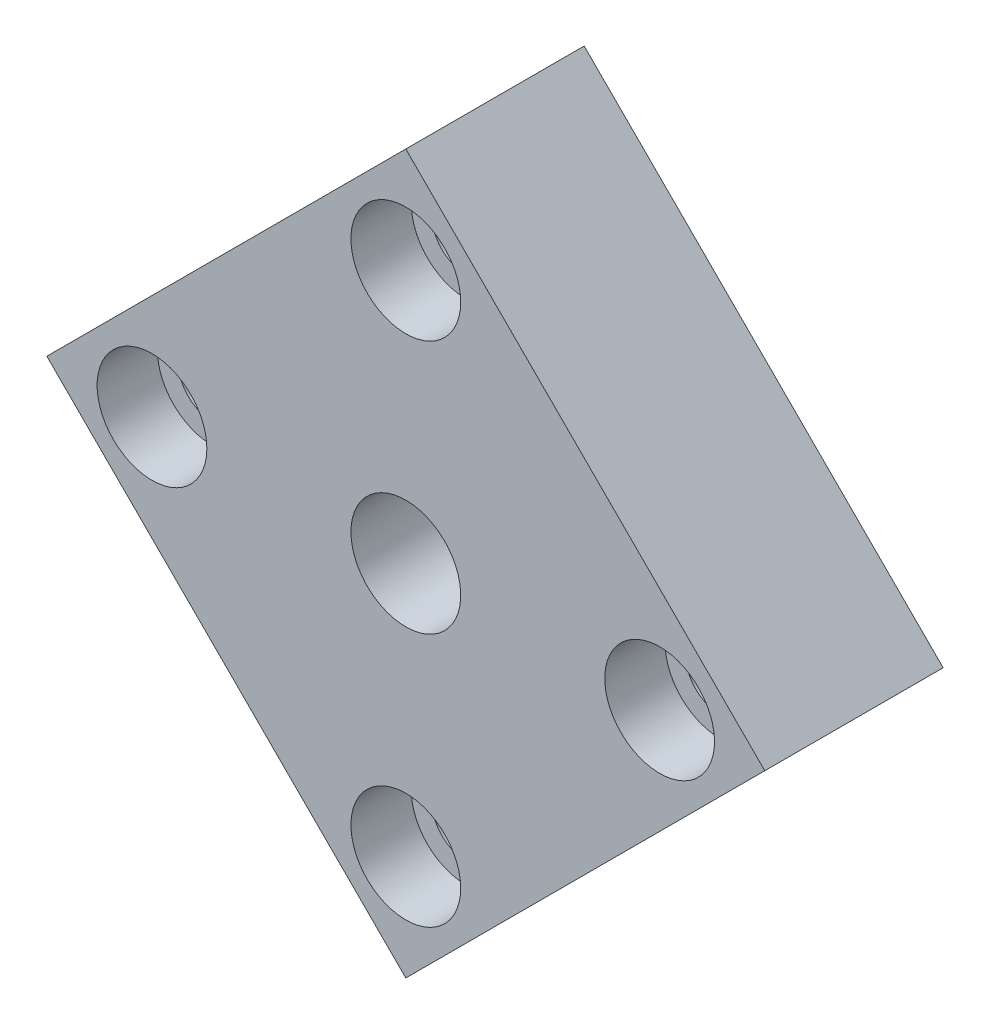
SolidWorks part; units mm, degrees
ref_plane "前视基准面" through (0, 0, 0) normal (0, 0, 1) x (1, 0, 0)
ref_plane "上视基准面" through (0, 0, 0) normal (0, 1, 0) x (1, 0, 0)
ref_plane "右视基准面" through (0, 0, 0) normal (1, 0, 0) x (0, 0, -1)
other "Configuration Table"
sketch "草图1" plane through (0, 0, 0) normal (0, 0, 1) x (1, 0, 0)
  line L1 (0, 26.163) -> (-26.163, 0)
  line L2 (-26.163, 0) -> (0, -26.163)
  line L3 (0, -26.163) -> (26.163, 0)
  line L4 (26.163, 0) -> (0, 26.163)
  circle A0 centre (0, 0) radius 18.5 construction
  circle A1 centre (18.5, 0) radius 2.5
  circle A2 centre (0, -18.5) radius 2.5
  circle A3 centre (0, 0) radius 18.5 construction
  circle A4 centre (-18.5, 0) radius 2.5
  circle A5 centre (0, 0) radius 18.5 construction
  circle A6 centre (0, 18.5) radius 2.5
  circle A7 centre (0, 0) radius 18.5 construction
  circle A8 centre (0, 0) radius 4
  point P21 (0, 0)
  dimension "D2" = 5
  dimension "D4" = 8
  dimension "D1" = 37
  dimension "D3" = 4
extrude "凸台-拉伸1" add sketch "草图1" along normal blind 13
sketch "草图2" plane through (0, 0, 13) normal (0, 0, 1) x (1, 0, 0)
  circle A0 centre (0, 0) radius 18.5 construction
  circle A1 centre (18.5, 0) radius 4
  circle A2 centre (0, -18.5) radius 4
  circle A3 centre (0, 0) radius 18.5 construction
  circle A4 centre (-18.5, 0) radius 4
  circle A5 centre (0, 0) radius 18.5 construction
  circle A6 centre (0, 18.5) radius 4
  circle A7 centre (0, 0) radius 18.5 construction
  point P18 (0, 0)
  dimension "D1" = 8
  dimension "D2" = 4
extrude "切除-拉伸1" cut sketch "草图2" against normal blind 4.4
